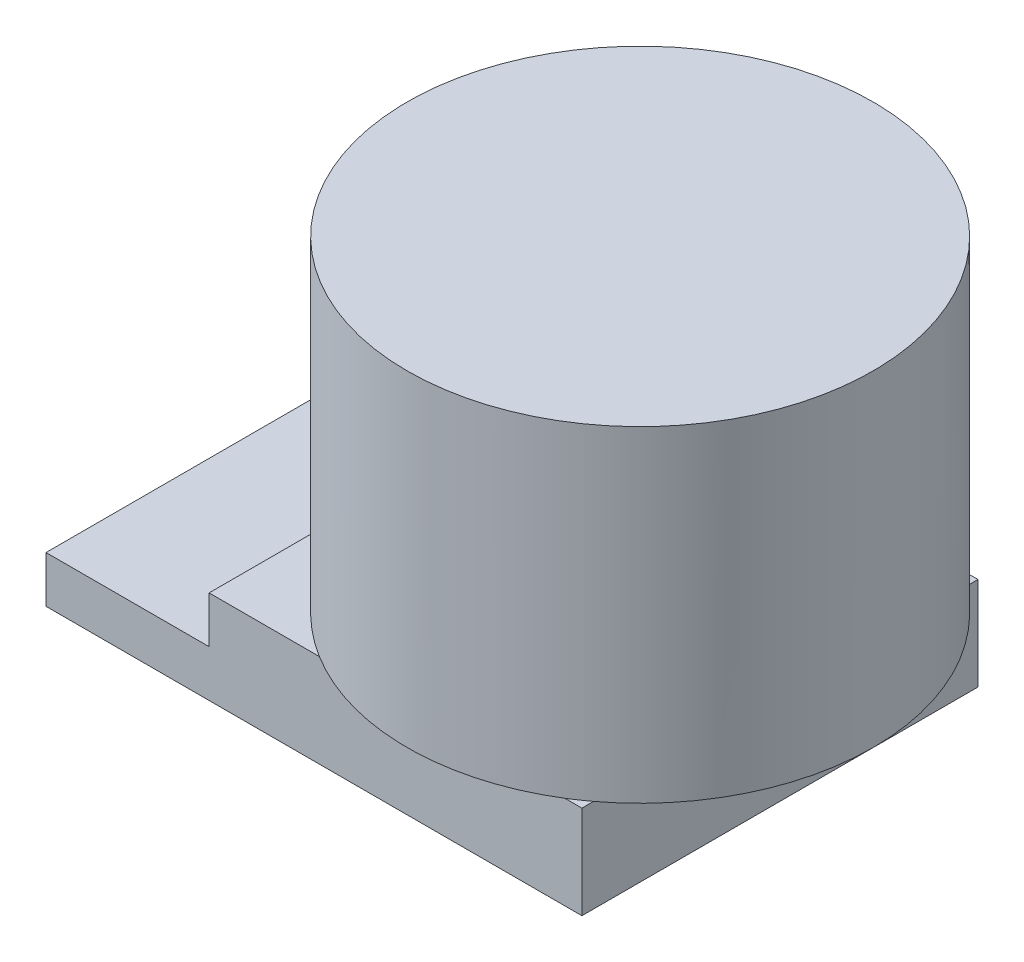
SolidWorks part; units mm, degrees
ref_plane "Front Plane" through (0, 0, 0) normal (0, 0, 1) x (1, 0, 0)
ref_plane "Top Plane" through (0, 0, 0) normal (0, 1, 0) x (1, 0, 0)
ref_plane "Right Plane" through (0, 0, 0) normal (1, 0, 0) x (0, 0, -1)
sketch "Sketch1" plane through (0, 0, 0) normal (0, 1, 0) x (1, 0, 0)
  line L1 (-5.75, 4.25) -> (5.75, 4.25)
  line L2 (-5.75, 4.25) -> (-5.75, -4.25)
  line L3 (-5.75, -4.25) -> (5.75, -4.25)
  line L4 (5.75, 4.25) -> (5.75, -4.25)
  point P4 (-5.75, 0)
  point P6 (0, 4.25)
  dimension "D1" = 11.5
  dimension "D2" = 8.5
extrude "Boss-Extrude1" add sketch "Sketch1" along normal blind 2
sketch "Sketch2" plane through (0, 2, 0) normal (0, 1, 0) x (1, 0, 0)
  line L0 (5.75, -4.25) -> (5.75, 4.25) construction
  circle A0 centre (2.75, 0) radius 5
  point P4 (0, 0)
  dimension "D1" = 10
  dimension "D2" = 3
extrude "Boss-Extrude2" add sketch "Sketch2" along normal blind 7
sketch "Sketch3" plane through (0, 2, 0) normal (0, 1, 0) x (1, 0, 0)
  line L0 (-5.75, -4.25) -> (0.1161, -4.25) construction
  line L1 (-5.75, 4.25) -> (-2.25, 4.25)
  line L2 (-5.75, 4.25) -> (-5.75, -4.25)
  line L3 (-5.75, -4.25) -> (-2.25, -4.25)
  line L4 (-2.25, 4.25) -> (-2.25, -4.25)
  dimension "D1" = 3.5
extrude "Cut-Extrude1" cut sketch "Sketch3" against normal blind 1
